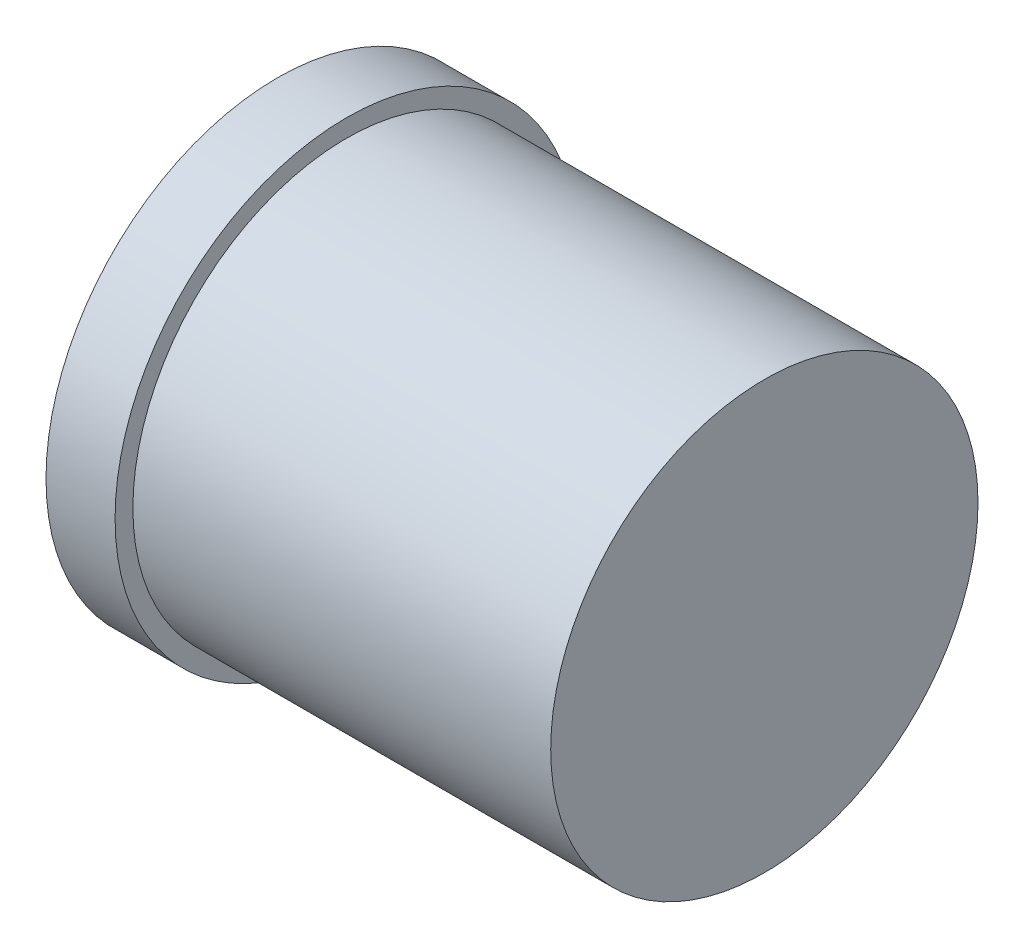
SolidWorks part; units mm, degrees
ref_plane "Front Plane" through (0, 0, 0) normal (0, 0, 1) x (1, 0, 0)
ref_plane "Top Plane" through (0, 0, 0) normal (0, 1, 0) x (1, 0, 0)
ref_plane "Right Plane" through (0, 0, 0) normal (1, 0, 0) x (0, 0, -1)
sketch "Sketch1" plane through (0, 0, 0) normal (1, 0, 0) x (0, 0, -1)
  circle A0 centre (0, 0) radius 27.7272
  circle A1 centre (0, 0) radius 38.1
  dimension "D1" = 55.4543
  dimension "D2" = 76.2
extrude "Boss-Extrude1" add sketch "Sketch1" along normal blind 26.9875
sketch "Sketch2" plane through (0, 0, 0) normal (-1, 0, 0) x (0, 0, 1)
  circle A0 centre (0, 0) radius 22.0345
  circle A1 centre (0, 0) radius 38.1
  circle A2 centre (0, 0) radius 38.1 construction
  dimension "D1" = 44.069
extrude "Boss-Extrude2" add sketch "Sketch2" along normal blind 5.5118
sketch "Sketch3" plane through (26.9875, 0, 0) normal (1, 0, 0) x (0, 0, -1)
  circle A0 centre (0, 0) radius 38.1
  circle A1 centre (0, 0) radius 22.0345
  circle A2 centre (0, 0) radius 38.1 construction
  circle A3 centre (0, 0) radius 22.0345 construction
extrude "Boss-Extrude3" add sketch "Sketch3" along normal blind 26.9875
sketch "Sketch4" plane through (0, 0, 0) normal (1, 0, 0) x (0, 0, -1)
  line L0 (0, 27.7272) -> (0, 0) construction
  line L1 (-2.1336, 21.931) -> (2.1336, 21.931) construction
  line L2 (-2.1336, 21.931) -> (-2.1336, 27.7272)
  line L3 (-2.1336, 27.7272) -> (2.1336, 27.7272)
  line L4 (2.1336, 21.931) -> (2.1336, 27.7272)
  circle A0 centre (0, 0) radius 22.0345 construction
  circle A1 centre (0, 0) radius 27.7272 construction
  arc A2 (-2.1336, 21.931) -> (2.1336, 21.931) centre (0, 0) cw
  dimension "D1" = 4.2672
extrude "Boss-Extrude4" add sketch "Sketch4" along normal blind 2.3876
mirror "Mirror1" about plane through (0, 0, 0) normal (0, 1, 0) of "Boss-Extrude4"
sketch "Sketch5" plane through (-5.5118, 0, 0) normal (-1, 0, 0) x (0, 0, 1)
  circle A0 centre (0, 0) radius 38.1
  circle A1 centre (0, 0) radius 17.526
  circle A2 centre (0, 0) radius 38.1 construction
  dimension "D1" = 35.052
extrude "Boss-Extrude5" add sketch "Sketch5" along normal blind 2.2098
ref_plane "Brush plate plane" through (39.4589, 0, 0) normal (-1, 0, 0) x (0, 0, 1)
sketch "Sketch7" plane through (39.4589, 0, 0) normal (-1, 0, 0) x (0, 0, 1)
  circle A0 centre (0, 0) radius 24.6062
  dimension "D1" = 49.2125
extrude "Cut-Extrude1" cut sketch "Sketch7" against normal blind 1.778
sketch "Sketch8" plane through (53.975, 0, 0) normal (1, 0, 0) x (0, 0, -1)
  circle A0 centre (0, 0) radius 38.1
  circle A1 centre (0, 0) radius 6.5151
  circle A2 centre (0, 0) radius 38.1 construction
  dimension "D1" = 13.0302
extrude "Boss-Extrude6" add sketch "Sketch8" along normal blind 5.969
sketch "Sketch9" plane through (59.944, 0, 0) normal (1, 0, 0) x (0, 0, -1)
  circle A0 centre (0, 0) radius 38.1
  circle A1 centre (0, 0) radius 5.0165
  circle A2 centre (0, 0) radius 38.1 construction
  dimension "D1" = 10.033
extrude "Boss-Extrude7" add sketch "Sketch9" along normal blind 5.2578
sketch "Sketch10" plane through (65.2018, 0, 0) normal (1, 0, 0) x (0, 0, -1)
  circle A0 centre (0, 0) radius 38.1
  circle A1 centre (0, 0) radius 38.1 construction
extrude "Boss-Extrude8" add sketch "Sketch10" along normal blind 1.5875
sketch "Sketch11" plane through (41.2369, 0, 0) normal (-1, 0, 0) x (0, 0, 1)
  line L0 (0, -24.6063) -> (0, 0) construction
  line L1 (1.8034, -21.9606) -> (-1.8034, -21.9606) construction
  line L2 (1.8034, -21.9606) -> (1.8034, -24.6063)
  line L3 (1.8034, -24.6063) -> (-1.8034, -24.6063)
  line L4 (-1.8034, -21.9606) -> (-1.8034, -24.6063)
  arc A0 (1.8034, -21.9606) -> (-1.8034, -21.9606) centre (0, 0) cw
  circle A1 centre (0, 0) radius 22.0345 construction
  circle A2 centre (0, 0) radius 24.6063 construction
  dimension "D1" = 3.6068
extrude "Boss-Extrude9" add sketch "Sketch11" along normal up to next
mirror "Mirror2" about plane through (0, 0, 0) normal (0, 1, 0) of "Boss-Extrude9"
sketch "Sketch12" plane through (-7.7216, 0, 0) normal (-1, 0, 0) x (0, 0, 1)
  circle A0 centre (0, 0) radius 31.75
  circle A1 centre (0, 0) radius 41.275
  dimension "D1" = 63.5
  dimension "D2" = 82.55
extrude "Boss-Extrude10" add sketch "Sketch12" along normal blind 12.319
